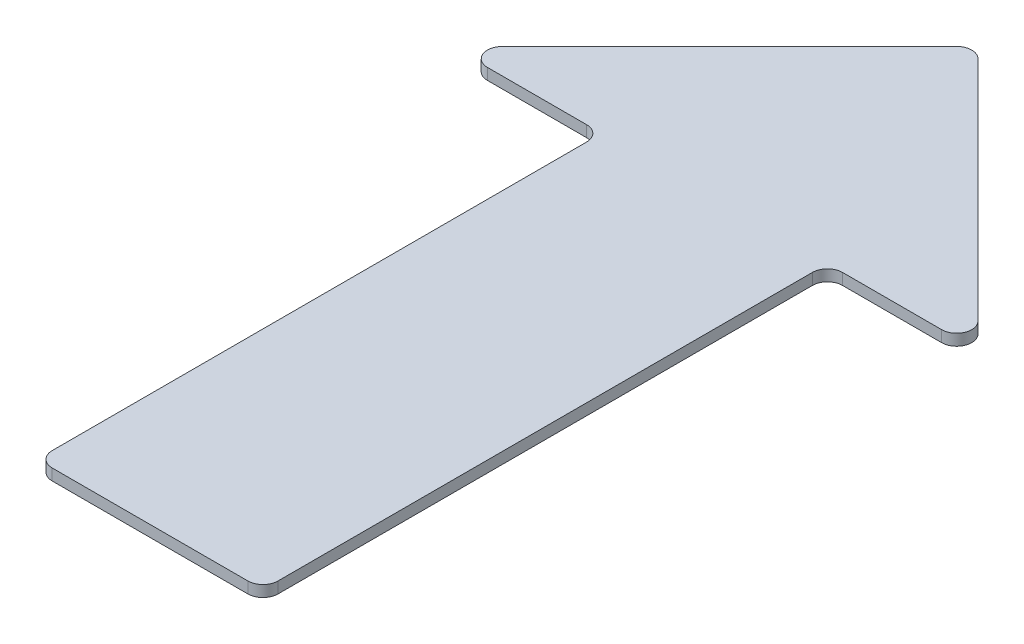
SolidWorks part; units mm, degrees
ref_plane "Front" through (0, 0, 0) normal (0, 0, 1) x (1, 0, 0)
ref_plane "Top" through (0, 0, 0) normal (0, 1, 0) x (1, 0, 0)
ref_plane "Right" through (0, 0, 0) normal (1, 0, 0) x (0, 0, -1)
sketch "Sketch1" plane through (0, 0, 0) normal (0, 1, 0) x (1, 0, 0)
  line L0 (0, 0) -> (0, -110) construction
  line L1 (0, 0) -> (35, -35)
  line L2 (35, -35) -> (15, -35)
  line L3 (15, -35) -> (15, -110)
  line L4 (15, -110) -> (-15, -110)
  line L5 (-15, -35) -> (-15, -110)
  line L6 (-35, -35) -> (-15, -35)
  line L7 (0, 0) -> (-35, -35)
  dimension "D1" = 110
  dimension "D2" = 30
  dimension "D3" = 90
  dimension "D4" = 35
extrude "Boss-Extrude1" add sketch "Sketch1" along normal blind 1.5
fillet "Fillet1" radius 2 7 edges at (0, 0.75, 0) (35, 0.75, 35) (15, 0.75, 35) (-15, 0.75, 110) (-15, 0.75, 35) (-35, 0.75, 35) (15, 0.75, 110)
